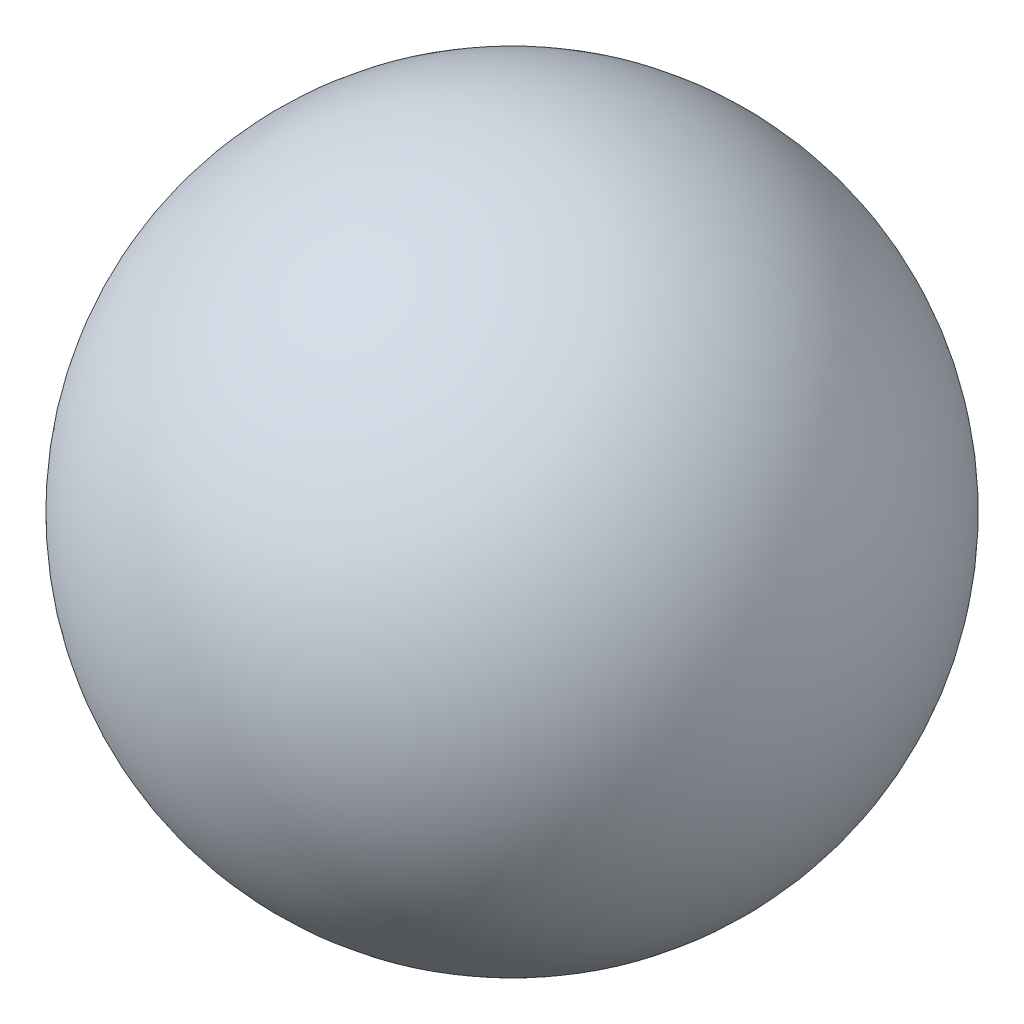
SolidWorks part; units mm, degrees
ref_plane "Piano frontale" through (0, 0, 0) normal (0, 0, 1) x (1, 0, 0)
ref_plane "Piano superiore" through (0, 0, 0) normal (0, 1, 0) x (1, 0, 0)
ref_plane "Piano destro" through (0, 0, 0) normal (1, 0, 0) x (0, 0, -1)
sketch "Schizzo1" plane through (0, 0, 0) normal (0, 0, 1) x (1, 0, 0)
  line L0 (0, 4) -> (0, -4)
  arc A0 (0, 4) -> (0, -4) centre (0, 0) ccw
  dimension "D1" = 8
revolve "Rivoluzione1" add sketch "Schizzo1" angle 360 about L0
